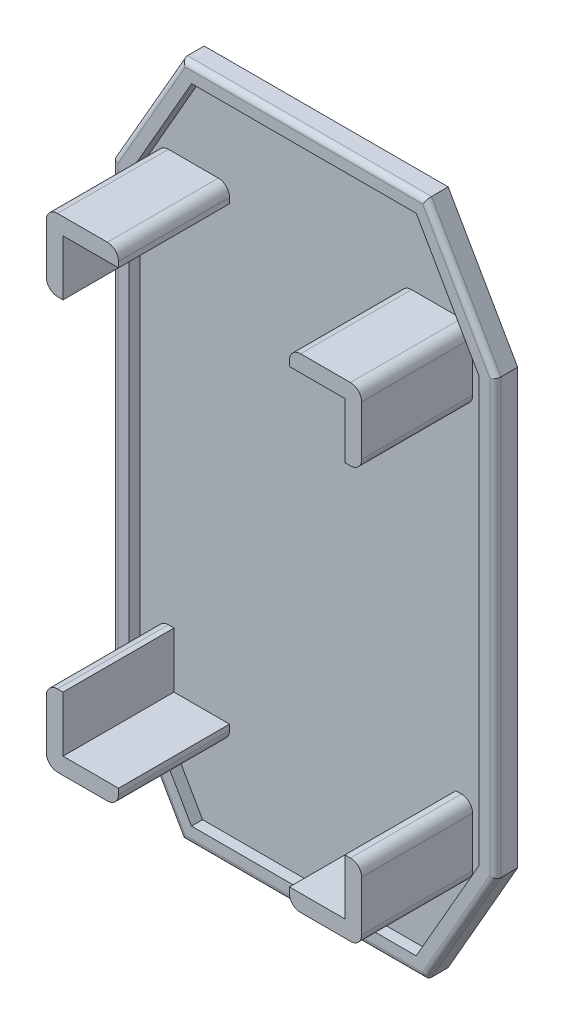
SolidWorks part; units mm, degrees
ref_plane "Front Plane" through (0, 0, 0) normal (0, 0, 1) x (1, 0, 0)
ref_plane "Top Plane" through (0, 0, 0) normal (0, 1, 0) x (1, 0, 0)
ref_plane "Right Plane" through (0, 0, 0) normal (1, 0, 0) x (0, 0, -1)
sketch "Sketch1" plane through (0, 0, 0) normal (0, 0, 1) x (1, 0, 0)
  line L0 (-18.0076, 19.7367) -> (-18.0076, -19.7274)
  line L5 (0, 0) -> (0, 40) construction
  line L6 (0, 0) -> (40, 0) construction
  line L11 (-17.2576, 19.5367) -> (-17.2576, -19.528) construction
  line L12 (-17.2576, -19.528) -> (-10.9981, -30.4692) construction
  line L13 (-18.0076, -19.7274) -> (-11.4331, -31.2192)
  line L14 (-11.4331, -31.2192) -> (11.4169, -31.2192)
  line L15 (11.4169, -31.2192) -> (18.0076, -19.7367)
  line L16 (18.0076, -19.7367) -> (18.0076, 19.7274)
  line L17 (18.0076, 19.7274) -> (11.4331, 31.2192)
  line L18 (11.4331, 31.2192) -> (-11.4169, 31.2192)
  line L19 (-11.4169, 31.2192) -> (-18.0076, 19.7367)
  line L20 (-10.9981, -30.4692) -> (10.9826, -30.4692) construction
  line L21 (10.9826, -30.4692) -> (17.2576, -19.5367) construction
  line L22 (17.2576, -19.5367) -> (17.2576, 19.528) construction
  line L23 (17.2576, 19.528) -> (10.9981, 30.4692) construction
  line L24 (10.9981, 30.4692) -> (-10.9826, 30.4692) construction
  line L25 (-10.9826, 30.4692) -> (-17.2576, 19.5367) construction
  point P0 (0, 0)
  point P1 (0, 0)
  point P5 (0, 0)
  dimension "D1" = 22.85
  dimension "D2" = 40
  dimension "D3" = 39.4641
  dimension "D4" = 40
  dimension "D5" = 0.75
  dimension "D7" = 31.2192
  dimension "D8" = 18.0076
extrude "Boss-Extrude1" add sketch "Sketch1" along normal blind 1
sketch "Sketch2" plane through (0, 0, 1) normal (0, 0, 1) x (1, 0, 0)
  line L8 (-10.1141, 28.9692) -> (-15.7576, 19.1369)
  line L9 (-15.7576, 19.1369) -> (-15.7576, -19.1293)
  line L10 (-15.7576, -19.1293) -> (-10.1281, -28.9692)
  line L11 (-10.1281, -28.9692) -> (10.1141, -28.9692)
  line L12 (10.1141, -28.9692) -> (15.7576, -19.1369)
  line L13 (15.7576, -19.1369) -> (15.7576, 19.1293)
  line L14 (15.7576, 19.1293) -> (10.1281, 28.9692)
  line L15 (10.1281, 28.9692) -> (-10.1141, 28.9692)
  line L16 (-10.9826, 30.4692) -> (-17.2576, 19.5367)
  line L17 (-17.2576, 19.5367) -> (-17.2576, -19.528)
  line L18 (-17.2576, -19.528) -> (-10.9981, -30.4692)
  line L19 (-10.9981, -30.4692) -> (10.9826, -30.4692)
  line L20 (10.9826, -30.4692) -> (17.2576, -19.5367)
  line L21 (17.2576, -19.5367) -> (17.2576, 19.528)
  line L22 (17.2576, 19.528) -> (10.9981, 30.4692)
  line L23 (10.9981, 30.4692) -> (-10.9826, 30.4692)
  line L24 (-10.9826, 30.4692) -> (-17.2576, 19.5367)
  line L25 (-17.2576, 19.5367) -> (-17.2576, -19.528)
  line L26 (-17.2576, -19.528) -> (-10.9981, -30.4692)
  line L27 (-10.9981, -30.4692) -> (10.9826, -30.4692)
  line L28 (10.9826, -30.4692) -> (17.2576, -19.5367)
  line L29 (17.2576, -19.5367) -> (17.2576, 19.528)
  line L30 (17.2576, 19.528) -> (10.9981, 30.4692)
  line L31 (10.9981, 30.4692) -> (-10.9826, 30.4692)
  dimension "D1" = 0.75
  dimension "D2" = 1.5
extrude "Boss-Extrude2" add sketch "Sketch2" along normal blind 1
sketch "Sketch3" plane through (0, 0, 1) normal (0, 0, 1) x (1, 0, 0)
  line L5 (-14.2, -21.8) -> (-14.2, -15.3)
  line L6 (-12.7, -20.3) -> (-7.7, -20.3)
  line L12 (-12.7, -20.3) -> (-12.7, -15.3)
  line L14 (-12.7, 20.3) -> (-7.7, 20.3)
  line L16 (12.7, -20.3) -> (12.7, -15.3)
  line L19 (-12.7, -20.3) -> (12.7, 20.3) construction
  line L21 (-12.7, 20.3) -> (12.7, -20.3) construction
  line L23 (-14.2, 21.8) -> (-7.7, 21.8)
  line L24 (14.2, -21.8) -> (14.2, -15.3)
  line L25 (-14.2, -21.8) -> (-7.7, -21.8)
  line L26 (-12.7, 15.3) -> (-14.2, 15.3)
  line L27 (-7.7, 20.3) -> (-7.7, 21.8)
  line L28 (0, 21.3578) -> (0, 0) construction
  line L29 (0, 0) -> (20.1756, 0) construction
  line L30 (12.7, 15.3) -> (14.2, 15.3)
  line L31 (7.7, 20.3) -> (7.7, 21.8)
  line L32 (12.7, -15.3) -> (14.2, -15.3)
  line L33 (7.7, -20.3) -> (7.7, -21.8)
  line L34 (-7.7, -20.3) -> (-7.7, -21.8)
  line L35 (-12.7, -15.3) -> (-14.2, -15.3)
  line L36 (-12.7, 15.3) -> (-12.7, 20.3)
  line L37 (-12.7, -20.3) -> (-12.7, 20.3) construction
  line L38 (-14.2, 15.3) -> (-14.2, 21.8)
  line L39 (-14.2, -21.8) -> (-14.2, 21.8) construction
  line L40 (12.7, 15.3) -> (12.7, 20.3)
  line L41 (12.7, -20.3) -> (12.7, 20.3) construction
  line L42 (14.2, 15.3) -> (14.2, 21.8)
  line L43 (14.2, -21.8) -> (14.2, 21.8) construction
  line L44 (7.7, -21.8) -> (14.2, -21.8)
  line L45 (-14.2, -21.8) -> (14.2, -21.8) construction
  line L46 (7.7, -20.3) -> (12.7, -20.3)
  line L47 (-12.7, -20.3) -> (12.7, -20.3) construction
  line L48 (7.7, 20.3) -> (12.7, 20.3)
  line L49 (-12.7, 20.3) -> (12.7, 20.3) construction
  line L50 (7.7, 21.8) -> (14.2, 21.8)
  line L51 (-14.2, 21.8) -> (14.2, 21.8) construction
  point P0 (0, 0)
  dimension "D4" = 5
  dimension "D1" = 40.6
  dimension "D2" = 25.4
  dimension "D5" = 5
  dimension "D3" = 1.5
extrude "Boss-Extrude3" add sketch "Sketch3" along normal blind 10
sketch "Sketch4" plane through (0, 0, 1) normal (0, 0, 1) x (1, 0, 0)
  line L8 (10.9981, 30.4692) -> (-10.9826, 30.4692)
  line L9 (-10.9826, 30.4692) -> (-17.2576, 19.5367)
  line L10 (-17.2576, 19.5367) -> (-17.2576, -19.528)
  line L11 (-17.2576, -19.528) -> (-10.9981, -30.4692)
  line L12 (-10.9981, -30.4692) -> (10.9826, -30.4692)
  line L13 (10.9826, -30.4692) -> (17.2576, -19.5367)
  line L14 (17.2576, -19.5367) -> (17.2576, 19.528)
  line L15 (17.2576, 19.528) -> (10.9981, 30.4692)
  line L16 (10.9981, 30.4692) -> (-10.9826, 30.4692)
  line L17 (-10.9826, 30.4692) -> (-17.2576, 19.5367)
  line L18 (-17.2576, 19.5367) -> (-17.2576, -19.528)
  line L19 (-17.2576, -19.528) -> (-10.9981, -30.4692)
  line L20 (-10.9981, -30.4692) -> (10.9826, -30.4692)
  line L21 (10.9826, -30.4692) -> (17.2576, -19.5367)
  line L22 (17.2576, -19.5367) -> (17.2576, 19.528)
  line L23 (17.2576, 19.528) -> (10.9981, 30.4692)
  line L32 (13.898, 35.4692) -> (-13.8779, 35.4692)
  line L33 (-13.8779, 35.4692) -> (-22.2576, 20.8697)
  line L34 (-22.2576, 20.8697) -> (-22.2576, -20.8572)
  line L35 (-22.2576, -20.8572) -> (-13.898, -35.4692)
  line L36 (-13.898, -35.4692) -> (13.8779, -35.4692)
  line L37 (13.8779, -35.4692) -> (22.2576, -20.8697)
  line L38 (22.2576, -20.8697) -> (22.2576, 20.8572)
  line L39 (22.2576, 20.8572) -> (13.898, 35.4692)
  line L40 (13.898, 35.4692) -> (-13.8779, 35.4692)
  line L41 (-13.8779, 35.4692) -> (-22.2576, 20.8697)
  line L42 (-22.2576, 20.8697) -> (-22.2576, -20.8572)
  line L43 (-22.2576, -20.8572) -> (-13.898, -35.4692)
  line L44 (-13.898, -35.4692) -> (13.8779, -35.4692)
  line L45 (13.8779, -35.4692) -> (22.2576, -20.8697)
  line L46 (22.2576, -20.8697) -> (22.2576, 20.8572)
  line L47 (22.2576, 20.8572) -> (13.898, 35.4692)
  dimension "D1" = 0
  dimension "D2" = 5
extrude "Cut-Extrude1" cut sketch "Sketch4" against normal blind 6.35
fillet "Fillet1" radius 1 12 edges at (-14.2, 21.8, 6) (14.2, 21.8, 6) (14.2, -21.8, 6) (-14.2, -21.8, 6) (-14.2, 15.3, 6) (-7.7, 21.8, 6) (7.7, 21.8, 6) (14.2, 15.3, 6) (14.2, -15.3, 6) (7.7, -21.8, 6) (-7.7, -21.8, 6) (-14.2, -15.3, 6)
fillet "Fillet2" radius 0.5 8 edges at (14.1278, 24.9986, 2) (17.2576, -0.0043, 2) (14.1201, -25.003, 2) (-0.0077, -30.4692, 2) (-14.1201, 25.003, 2) (0.0077, 30.4692, 2) (-14.1278, -24.9986, 2) (-17.2576, 0.0043, 2)
